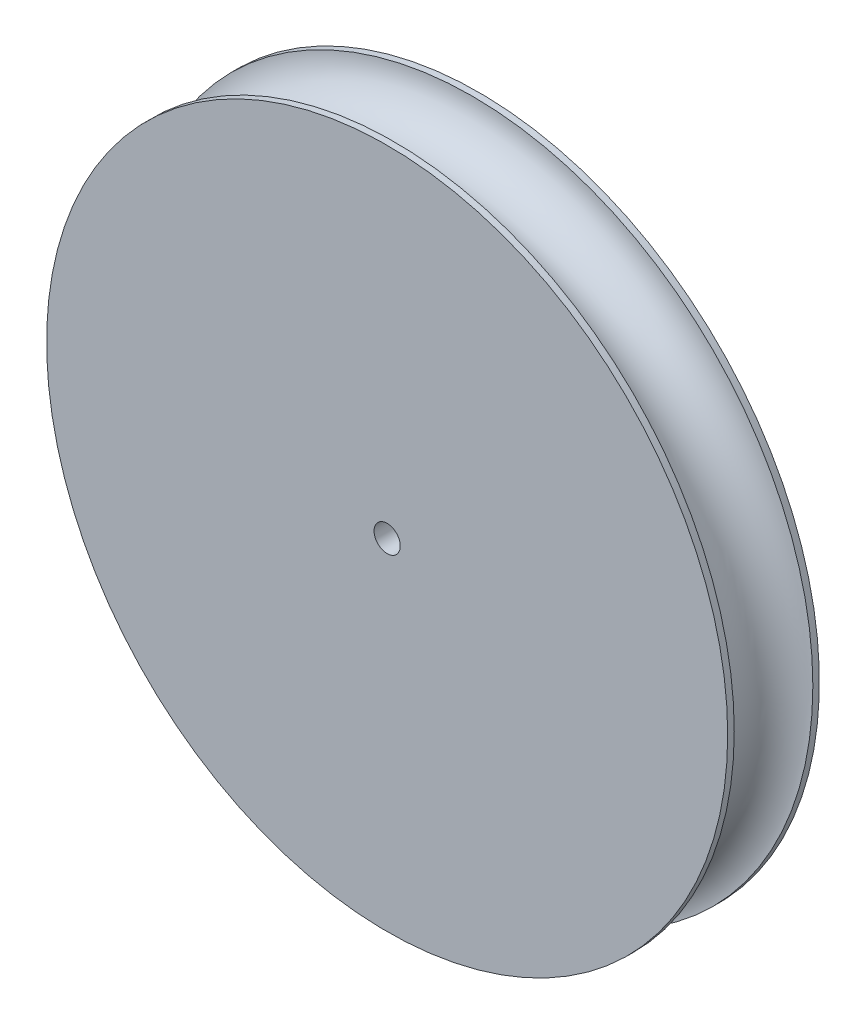
SolidWorks part; units mm, degrees
ref_plane "Front Plane" through (0, 0, 0) normal (0, 0, 1) x (1, 0, 0)
ref_plane "Top Plane" through (0, 0, 0) normal (0, 1, 0) x (1, 0, 0)
ref_plane "Right Plane" through (0, 0, 0) normal (1, 0, 0) x (0, 0, -1)
sketch "Sketch1" plane through (0, 0, 0) normal (0, 1, 0) x (1, 0, 0)
  line L0 (23, 0) -> (35.6534, 0) construction
  line L1 (0, 0) -> (23, 0)
  line L2 (0, 0) -> (0, 6)
  line L3 (0, 6) -> (23, 6)
  line L4 (23, 0) -> (23, 6)
  line L5 (23, 6) -> (36.1226, 6) construction
  line L6 (23, 6) -> (26, 6)
  line L7 (23, 0) -> (26, 0)
  circle A0 centre (26, 3) radius 3
revolve "Revolve1" add sketch "Sketch1" angle 360 about L2
sketch "Sketch2" plane through (0, 0, 0) normal (0, 0, 1) x (1, 0, 0)
  circle A0 centre (0, 0) radius 1
  circle A1 centre (0, 0) radius 26
extrude "Boss-Extrude1" add sketch "Sketch2" along normal blind 0.5
sketch "Sketch3" plane through (0, 0, -6) normal (0, 0, -1) x (-1, 0, 0)
  circle A0 centre (0, 0) radius 26
extrude "Boss-Extrude2" add sketch "Sketch3" along normal blind 0.5
sketch "Sketch4" plane through (0, 0, -6.5) normal (0, 0, -1) x (-1, 0, 0)
  circle A0 centre (0, 0) radius 1
extrude "Cut-Extrude2" cut sketch "Sketch4" against normal up to surface (7 mm away) up to face at (26, 0, 0.5)
